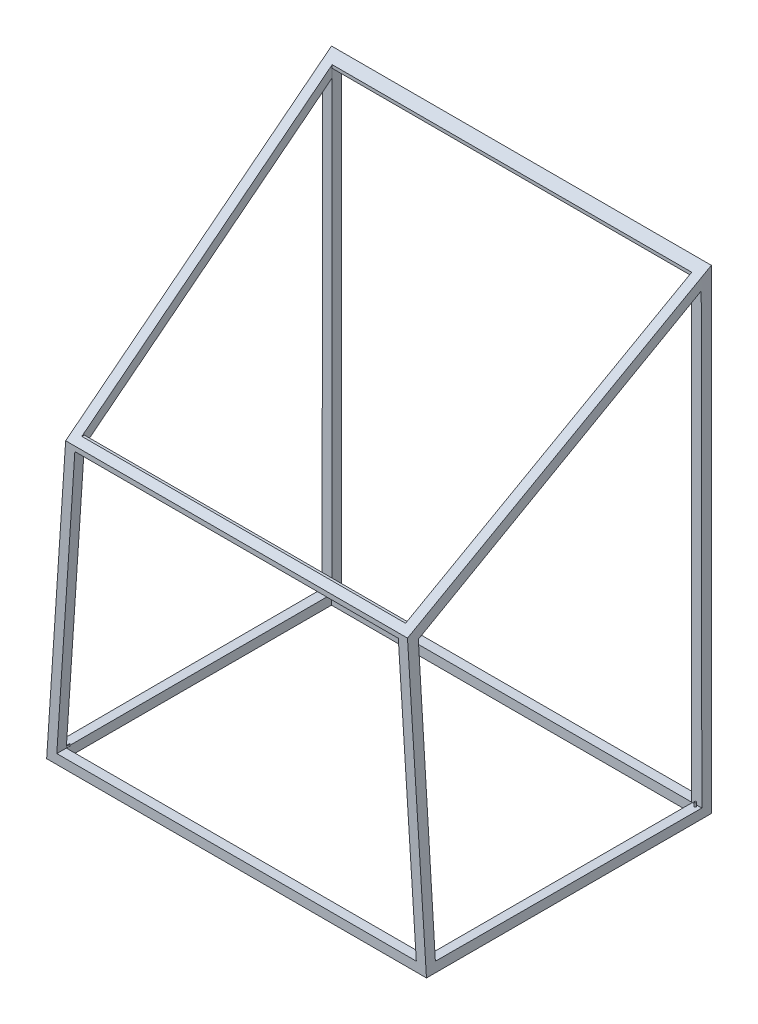
SolidWorks part; units mm, degrees
material "Thornel Mat VMA"
ref_plane "Plan de face" through (0, 0, 0) normal (0, 0, 1) x (1, 0, 0)
ref_plane "Plan de dessus" through (0, 0, 0) normal (0, 1, 0) x (1, 0, 0)
ref_plane "Plan de droite" through (0, 0, 0) normal (1, 0, 0) x (0, 0, -1)
sketch "Esquisse1" plane through (0, 0, 0) normal (0, 0, 1) x (1, 0, 0)
  line L1 (-732.0815, 1298.893) -> (1267.9185, 1298.893)
  line L2 (-732.0815, 1298.893) -> (-732.0815, -1201.107)
  line L3 (-732.0815, -1201.107) -> (1267.9185, -1201.107)
  line L4 (1267.9185, 1298.893) -> (1267.9185, -1201.107)
  dimension "D1" = 2000
  dimension "D2" = 2500
ref_plane "Plan1" through (0, 0, 1500) normal (0, 0, 1) x (1, 0, 0)
sketch "Esquisse2" plane through (0, 0, 1500) normal (0, 0, 1) x (1, 0, 0)
  line L0 (-732.0815, -1201.107) -> (1267.9185, -1201.107)
  line L1 (1267.9185, -1201.107) -> (1167.9185, 298.893)
  line L2 (1167.9185, 298.893) -> (-632.0815, 298.893)
  line L3 (-632.0815, 298.893) -> (-732.0815, -1201.107)
  dimension "D1" = 1800
  dimension "D2" = 1500
loft "Lissage1" add profiles "Esquisse2", "Esquisse1"
sketch "Esquisse3" plane through (0, 0, 0) normal (1, 0, 0) x (0, 0, -1)
  line L0 (-1450, -1151.107) -> (-50, -1151.107)
  line L1 (-50, -1151.107) -> (-50, 1205.4671)
  line L2 (-50, 1205.4671) -> (-1450, 272.1338)
  line L3 (-1450, 272.1338) -> (-1450, -1151.107)
  line L4 (0, 1298.893) -> (-1500, 298.893) construction
  line L5 (0, -1201.107) -> (0, 1298.893) construction
  line L6 (-1500, -1201.107) -> (-1500, 298.893) construction
  line L7 (-1500, -1201.107) -> (0, -1201.107) construction
  dimension "D1" = 50
  dimension "D2" = 50
  dimension "D3" = 50
  dimension "D4" = 50
extrude "Enlèv. mat.-Extru.1" cut sketch "Esquisse3" against normal blind 1210 and the other way blind 1873
sketch "Esquisse4" plane through (0, 0, 0) normal (0, 0, 1) x (1, 0, 0)
  line L0 (-583.6371, 273.893) -> (-678.6371, -1151.107)
  line L1 (-678.6371, -1151.107) -> (1214.4742, -1151.107)
  line L2 (1214.4742, -1151.107) -> (1119.4742, 273.893)
  line L3 (1119.4742, 273.893) -> (-583.6371, 273.893)
  line L4 (-676.8321, 1248.893) -> (-584.3321, 323.893)
  line L5 (-584.3321, 323.893) -> (1120.1692, 323.893)
  line L6 (1120.1692, 323.893) -> (1212.6692, 1248.893)
  line L7 (1212.6692, 1248.893) -> (-676.8321, 1248.893)
  line L8 (-632.0815, 298.893) -> (-732.0815, 1298.893) construction
  line L9 (1267.9185, 1298.893) -> (1167.9185, 298.893) construction
  line L10 (-632.0815, 298.893) -> (-732.0815, -1201.107) construction
  line L11 (1267.9185, -1201.107) -> (1167.9185, 298.893) construction
  line L12 (1267.9185, 1298.893) -> (-732.0815, 1298.893) construction
  line L13 (1167.9185, 298.893) -> (-632.0815, 298.893) construction
  line L14 (-732.0815, -1201.107) -> (1267.9185, -1201.107) construction
  dimension "D1" = 50
  dimension "D2" = 50
  dimension "D3" = 50
  dimension "D4" = 25
  dimension "D5" = 25
  dimension "D6" = 50
  dimension "D7" = 50
  dimension "D8" = 50
extrude "Enlèv. mat.-Extru.2" cut sketch "Esquisse4" along normal blind 2794
sketch "Esquisse5" plane through (0, 0, 0) normal (0, 0, -1) x (-1, 0, 0)
  line L0 (678.6371, -1151.107) -> (-1214.4742, -1151.107) construction
  line L1 (-1212.6692, 1248.893) -> (678.6371, 1248.893)
  line L2 (-1212.6692, 1248.893) -> (-1212.6692, -1151.107)
  line L3 (-1212.6692, -1151.107) -> (678.6371, -1151.107)
  line L4 (678.6371, 1248.893) -> (678.6371, -1151.107)
extrude "Enlèv. mat.-Extru.3" cut sketch "Esquisse5" against normal blind 50
sketch "Esquisse6" plane through (0, 323.893, 0) normal (0, 1, 0) x (1, 0, 0)
  line L7 (-678.6371, -50) -> (-585.3038, -1450)
  line L8 (-585.3038, -1450) -> (1121.1409, -1450)
  line L9 (1121.1409, -1450) -> (1214.4742, -50)
  line L10 (1214.4742, -50) -> (-678.6371, -50)
  line L11 (-584.3321, -1462.5) -> (-676.8321, -75) construction
  line L12 (1212.6692, -75) -> (1120.1692, -1462.5) construction
  line L13 (1267.9185, 0) -> (-732.0815, 0) construction
  line L14 (-632.0815, -1500) -> (-732.0815, 0) construction
  line L15 (1267.9185, 0) -> (1167.9185, -1500) construction
  line L16 (1167.9185, -1500) -> (-632.0815, -1500) construction
  dimension "D1" = 50
  dimension "D2" = 50
  dimension "D3" = 50
  dimension "D4" = 50
sketch "Esquisse7" plane through (0, -1201.107, 0) normal (0, -1, 0) x (1, 0, 0)
  line L0 (-732.0815, 1500) -> (1267.9185, 1500) construction
  line L1 (-682.0815, 1450) -> (1217.9185, 1450)
  line L2 (-682.0815, 1450) -> (-682.0815, 50)
  line L3 (-682.0815, 50) -> (1217.9185, 50)
  line L4 (1217.9185, 1450) -> (1217.9185, 50)
  line L5 (-732.0815, 1500) -> (-732.0815, 0) construction
  line L6 (-732.0815, 0) -> (1267.9185, 0) construction
  line L7 (1267.9185, 1500) -> (1267.9185, 0) construction
  dimension "D1" = 50
  dimension "D2" = 50
  dimension "D3" = 50
  dimension "D4" = 50
extrude "Enlèv. mat.-Extru.5" cut sketch "Esquisse7" against normal blind 50
extrude "Enlèv. mat.-Extru.6" cut sketch "Esquisse6" against normal blind 877 and the other way blind 1354
sketch "Esquisse10" plane through (0, -1151.107, 0) normal (0, 1, 0) x (1, 0, 0)
  line L0 (1267.851, -50) -> (1217.9185, -50) construction
  line L1 (1217.9185, -50) -> (1217.9185, -1450) construction
  circle A0 centre (1242.8835, -60) radius 5
  dimension "D1" = 10
  dimension "D2" = 24.965
extrude "Boss.-Extru.1" add sketch "Esquisse10" along normal blind 20
sketch "Esquisse11" plane through (0, 0, 1450) normal (0, 0, -1) x (-1, 0, 0)
  line L0 (-1214.5546, -1151.107) -> (-1213.872, -1142.0745)
  line L5 (-1214.4742, -1151.107) -> (-1119.4742, 273.893) construction
  line L6 (-1213.872, -1142.0745) -> (-1217.236, -1142.0745)
  line L7 (-1217.236, -1142.0745) -> (-1217.9185, -1151.107)
  line L8 (-1217.9185, -1153.9983) -> (-1217.9185, -1151.107)
  arc A0 (-1214.5546, -1151.107) -> (-1217.9185, -1153.9983) centre (-1217.6822, -1150.8707) cw
extrude "Boss.-Extru.3" add sketch "Esquisse11" along normal blind 20
sketch "Esquisse12" plane through (0, 0, 0) normal (0, 0, -1) x (-1, 0, 0)
  line L0 (-267.9185, -1201.107) -> (-267.9185, -199.6944) construction
  line L1 (732.0815, -1201.107) -> (-1267.9185, -1201.107) construction
  line L2 (-1267.9185, -1201.107) -> (-1267.9185, 1298.893) construction
  line L4 (-267.9185, -870.5116) -> (-1267.9185, -870.5116) construction
  line L5 (-267.9185, -895.9214) -> (732.0815, -895.9214) construction
  line L6 (732.0815, 1298.893) -> (732.0815, -1201.107) construction
ref_plane "Plan2" through (267.9185, 0, 0) normal (1, 0, 0) x (0, 0, -1)
mirror "Symétrie1" about plane through (267.9185, 0, 0) normal (1, 0, 0) of "Boss.-Extru.3", "Boss.-Extru.1"
